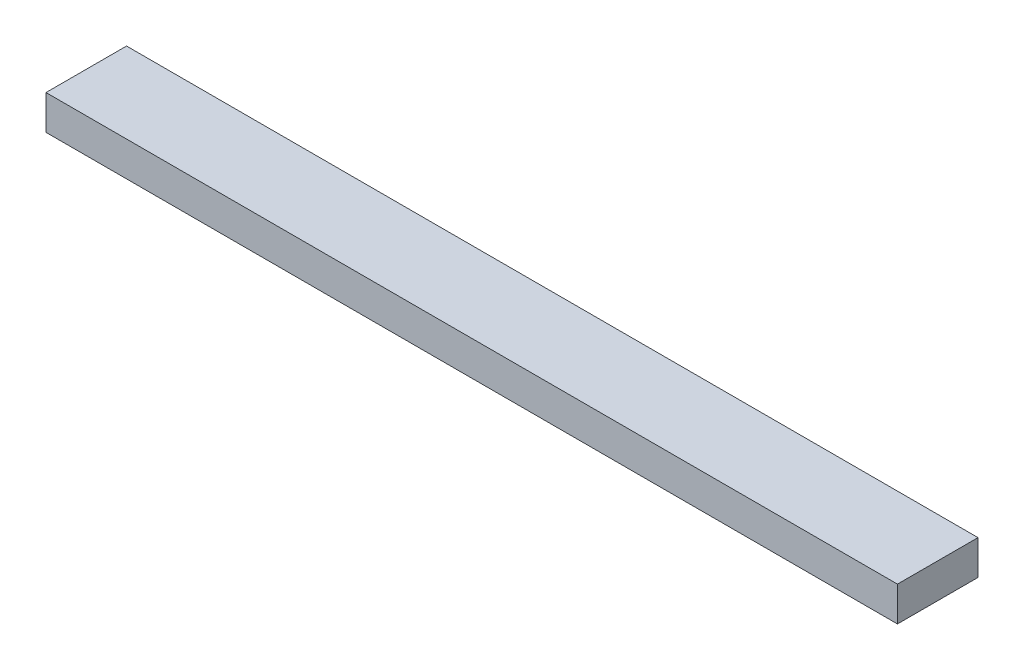
SolidWorks part; units mm, degrees
ref_plane "Front Plane" through (0, 0, 0) normal (0, 0, 1) x (1, 0, 0)
ref_plane "Top Plane" through (0, 0, 0) normal (0, 1, 0) x (1, 0, 0)
ref_plane "Right Plane" through (0, 0, 0) normal (1, 0, 0) x (0, 0, -1)
sketch "Sketch1" plane through (0, 0, 0) normal (0, 0, 1) x (1, 0, 0)
  line L1 (-469.8492, -19.05) -> (469.8492, -19.05)
  line L2 (-469.8492, -19.05) -> (-469.8492, 19.05)
  line L3 (-469.8492, 19.05) -> (469.8492, 19.05)
  line L4 (469.8492, -19.05) -> (469.8492, 19.05)
  line L5 (-469.8492, -19.05) -> (469.8492, 19.05) construction
  line L6 (-469.8492, 19.05) -> (469.8492, -19.05) construction
  point P0 (0, 0)
  dimension "D1" = 38.1
  dimension "D2" = 939.6984
extrude "Boss-Extrude1" add sketch "Sketch1" along normal blind 88.9
